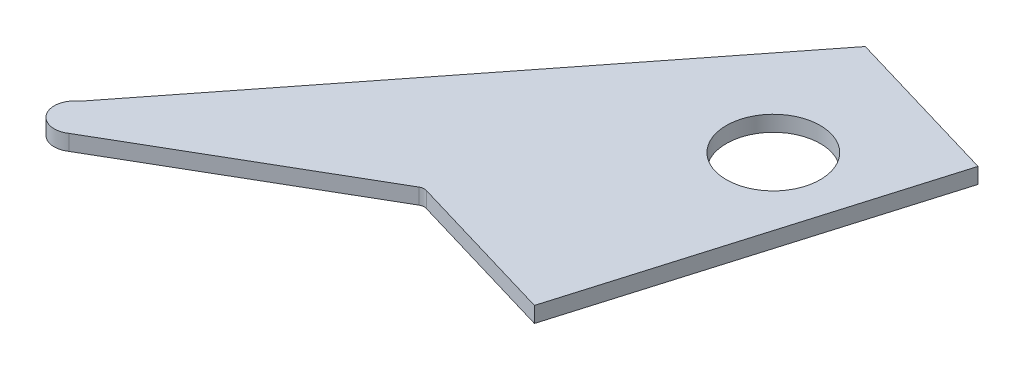
SolidWorks part; units mm, degrees
ref_plane "Front Plane" through (0, 0, 0) normal (0, 0, 1) x (1, 0, 0)
ref_plane "Top Plane" through (0, 0, 0) normal (0, 1, 0) x (1, 0, 0)
ref_plane "Right Plane" through (0, 0, 0) normal (1, 0, 0) x (0, 0, -1)
sketch "Sketch1" plane through (0, 0, 0) normal (0, 1, 0) x (1, 0, 0)
  line L0 (53.8544, 73.3734) -> (102.5625, 58.9454)
  line L1 (22.9946, -31.525) -> (-44.3261, -70.5626)
  line L2 (-51.2626, -60.5757) -> (53.8544, 73.3734)
  line L4 (102.5625, 58.9454) -> (71.7331, -45.1328)
  line L5 (71.7331, -45.1328) -> (24.9902, -31.2869)
  arc A0 (-44.3261, -70.5626) -> (-51.2626, -60.5757) centre (-47.7944, -65.5691) cw
  arc A2 (22.9946, -31.525) -> (24.9902, -31.2869) centre (24.2688, -33.7223) cw
  dimension "D1" = 2.54
extrude "Boss-Extrude1" add sketch "Sketch1" along normal blind 4.7625
sketch "Sketch2" plane through (0, 4.7625, 0) normal (0, 1, 0) x (1, 0, 0)
  circle A0 centre (67.8044, 31.4484) radius 14.2875
extrude "Cut-Extrude1" cut sketch "Sketch2" against normal through all
